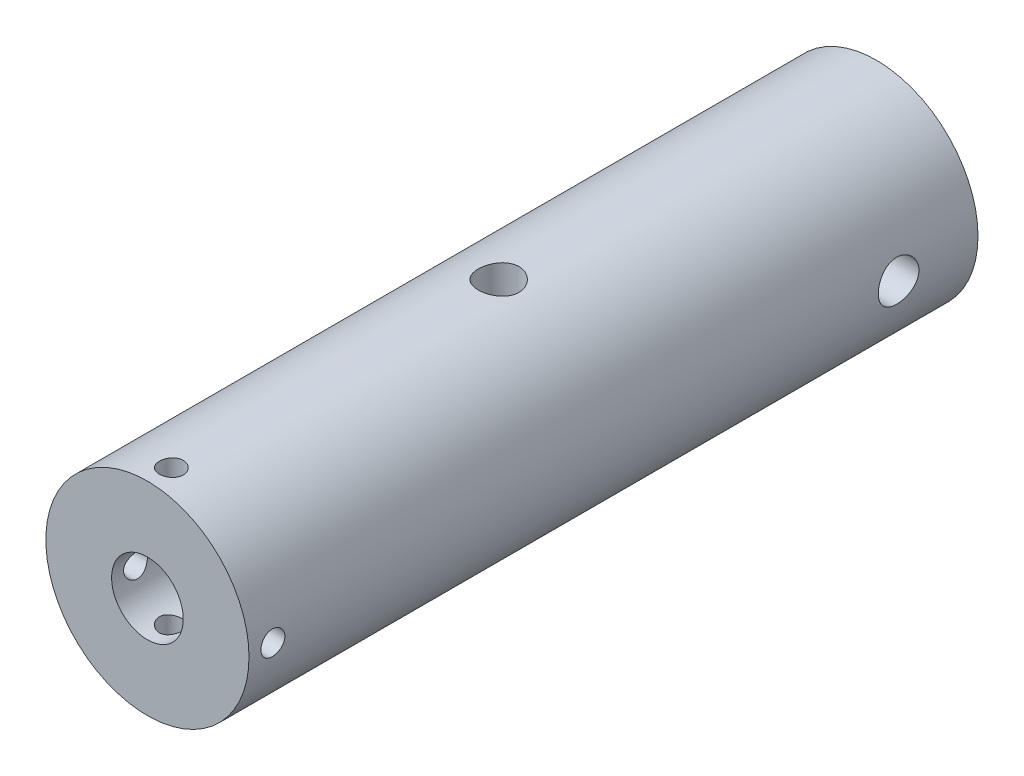
SolidWorks part; units mm, degrees
material "Alumina"
ref_plane "Front Plane" through (0, 0, 0) normal (0, 0, 1) x (1, 0, 0)
ref_plane "Top Plane" through (0, 0, 0) normal (0, 1, 0) x (1, 0, 0)
ref_plane "Right Plane" through (0, 0, 0) normal (1, 0, 0) x (0, 0, -1)
sketch "Sketch1" plane through (0, 0, 0) normal (0, 0, 1) x (1, 0, 0)
  circle A0 centre (0, 0) radius 8.5
  dimension "D1" = 17
extrude "Boss-Extrude1" add sketch "Sketch1" along normal blind 61
ref_plane "Plane1" through (0, 0, 0) normal (1, 0, 0) x (0, 0, -1)
ref_plane "Plane2" through (0, 0, 61) normal (0, 0, 1) x (1, 0, 0)
sketch "Sketch7" plane through (0, 0, 0) normal (1, 0, 0) x (0, 0, -1)
  line L0 (0, 0) -> (-64.6099, 0) construction
  line L1 (-64.6099, 0) -> (5.371, 0) construction
  line L2 (-61, 3) -> (-5, 3)
  line L3 (-61, 8.5) -> (-61, -8.5) construction
  line L4 (-5, 3) -> (-1, 1.5)
  line L5 (-1, 1.5) -> (0, 1.5)
  line L6 (0, -8.5) -> (0, 8.5) construction
  line L7 (0, 1.5) -> (0, 0)
  line L8 (-61, 3) -> (-61, 0)
  line L9 (0, 0) -> (-61, 0)
  point P8 (-0.5, 1.5)
  dimension "D1" = 4
  dimension "D2" = 1
  dimension "D3" = 1.5
  dimension "D4" = 3
revolve "Cut-Revolve1" cut sketch "Sketch7" angle 360 about L0
ref_plane "Plane3" through (8.5, 0, 0) normal (1, 0, 0) x (0, 0, -1)
sketch "Sketch9" plane through (8.5, 0, 0) normal (1, 0, 0) x (0, 0, -1)
  circle A0 centre (-6.6416, 0) radius 1.7
  dimension "D1" = 3.4
extrude "Cut-Extrude2" cut sketch "Sketch9" against normal blind 6.7
sketch "Sketch10" plane through (0, 0, 0) normal (1, 0, 0) x (0, 0, -1)
  line L0 (-61, 8.5) -> (-61, -8.5) construction
  circle A0 centre (-59, 0) radius 1
  dimension "D1" = 2
  dimension "D2" = 2
extrude "Cut-Extrude3" cut sketch "Sketch10" against normal blind 8.7
pattern_circular "CirPattern1" count 4 over 360 about axis through (0, 0, 61) along (0, 0, 1) of "Cut-Extrude3"
ref_plane "Plane4" through (0, 8.5, 0) normal (0, 1, 0) x (1, 0, 0)
sketch "Sketch11" plane through (0, 8.5, 0) normal (0, 1, 0) x (1, 0, 0)
  line L0 (0, 0) -> (0, -63.2228) construction
  line L1 (0, -63.2228) -> (0, -31.6114) construction
  line L2 (0, -31.6114) -> (12.403, -31.6114) construction
  line L3 (12.403, -31.6114) -> (-11.7433, -31.6114) construction
  circle A0 centre (0, -31.6114) radius 1.7
  dimension "D1" = 3.4
extrude "Cut-Extrude4" cut sketch "Sketch11" against normal blind 8.7
